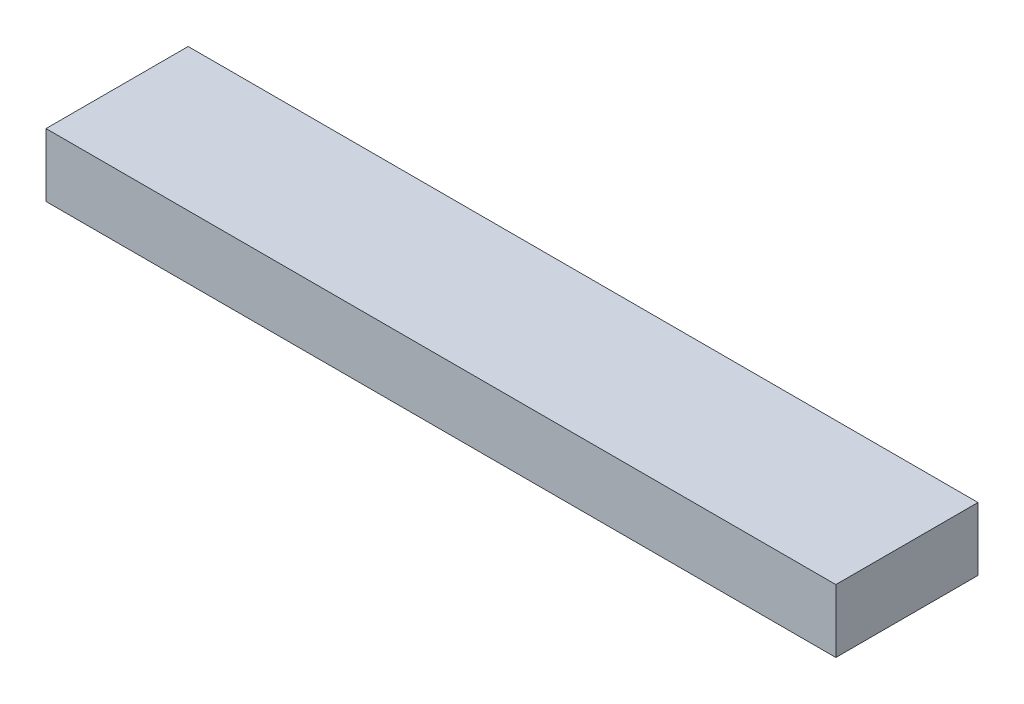
SolidWorks part; units mm, degrees
ref_plane "Front Plane" through (0, 0, 0) normal (0, 0, 1) x (1, 0, 0)
ref_plane "Top Plane" through (0, 0, 0) normal (0, 1, 0) x (1, 0, 0)
ref_plane "Right Plane" through (0, 0, 0) normal (1, 0, 0) x (0, 0, -1)
sketch "Sketch1" plane through (0, 0, 0) normal (0, 1, 0) x (1, 0, 0)
  line L1 (-125, 22.5) -> (125, 22.5)
  line L2 (-125, 22.5) -> (-125, -22.5)
  line L3 (-125, -22.5) -> (125, -22.5)
  line L4 (125, 22.5) -> (125, -22.5)
  line L5 (-125, 22.5) -> (125, -22.5) construction
  line L6 (-125, -22.5) -> (125, 22.5) construction
  point P0 (0, 0)
  dimension "D1" = 250
  dimension "D2" = 45
extrude "Boss-Extrude1" add sketch "Sketch1" along normal mid plane 20
